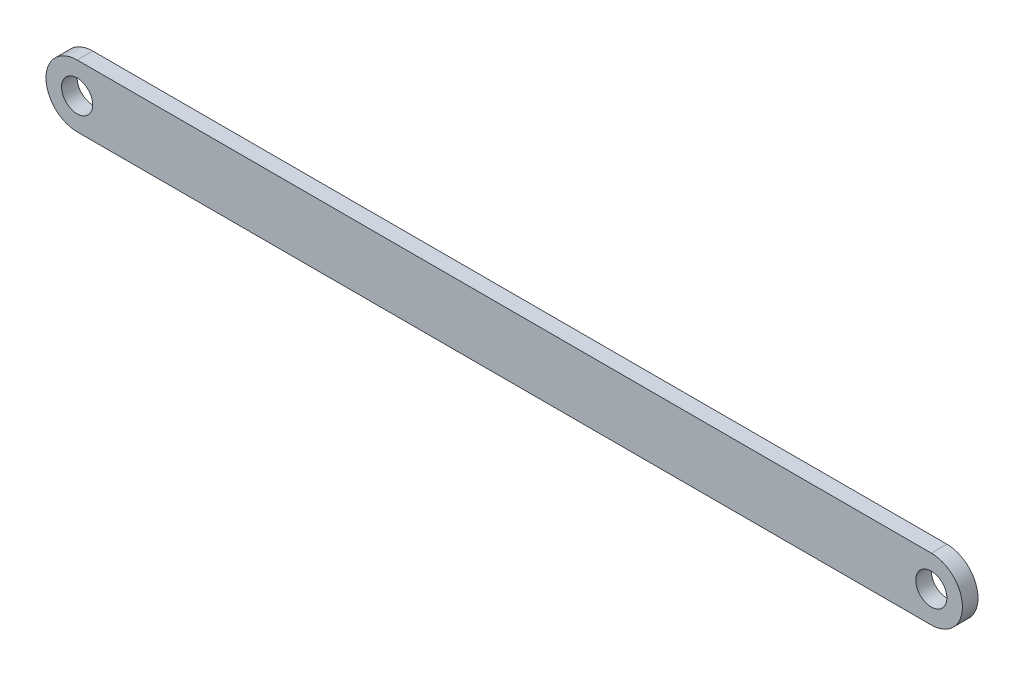
SolidWorks part; units mm, degrees
ref_plane "Plano frontal" through (0, 0, 0) normal (0, 0, 1) x (1, 0, 0)
ref_plane "Plano superior" through (0, 0, 0) normal (0, 1, 0) x (1, 0, 0)
ref_plane "Plano direito" through (0, 0, 0) normal (1, 0, 0) x (0, 0, -1)
sketch "Esboço1" plane through (0, 0, 0) normal (0, 0, 1) x (1, 0, 0)
  line L0 (-27.435, 2) -> (27.435, 2)
  line L1 (-27.435, 0) -> (27.435, 0) construction
  line L2 (-27.435, -2) -> (27.435, -2)
  arc A0 (-27.435, 2) -> (-27.435, -2) centre (-27.435, 0) ccw
  arc A1 (27.435, 2) -> (27.435, -2) centre (27.435, 0) cw
  circle A2 centre (-27.435, 0) radius 1
  circle A3 centre (27.435, 0) radius 1
  point P3 (0, 2)
  dimension "D1" = 54.87
  dimension "D2" = 2
extrude "Ressalto-extrusão1" add sketch "Esboço1" along normal blind 1
